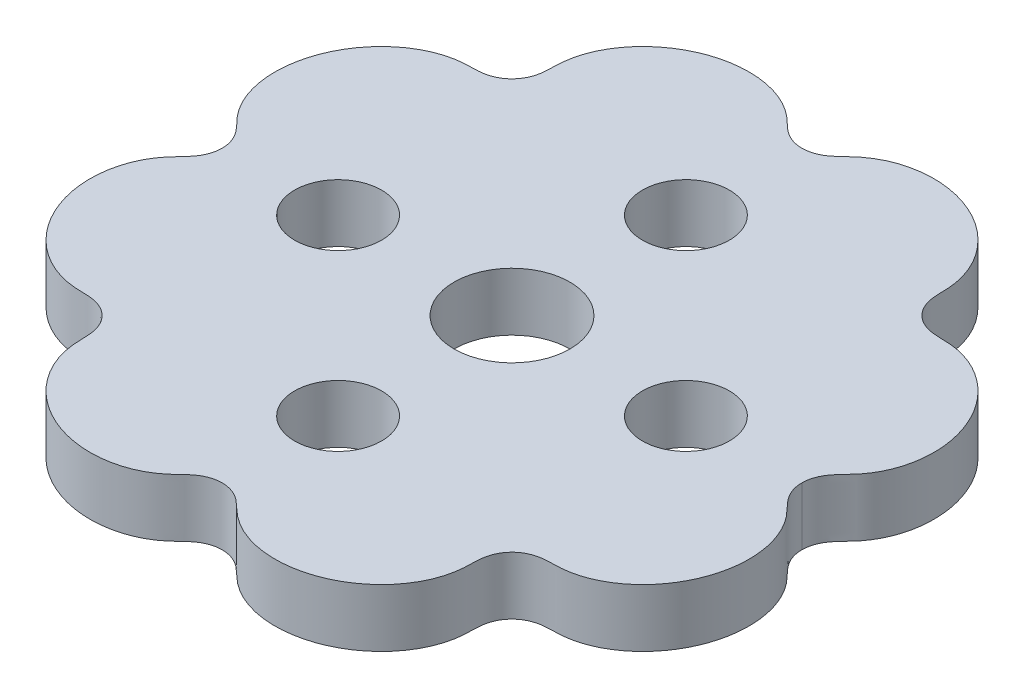
SolidWorks part; units mm, degrees
ref_plane "Front Plane" through (0, 0, 0) normal (0, 0, 1) x (1, 0, 0)
ref_plane "Top Plane" through (0, 0, 0) normal (0, 1, 0) x (1, 0, 0)
ref_plane "Right Plane" through (0, 0, 0) normal (1, 0, 0) x (0, 0, -1)
sketch "Sketch5" plane through (0, 0, 0) normal (0, 1, 0) x (1, 0, 0)
  line L0 (-32.3493, 0) -> (56.6401, 0)
  spline S0 degree 4 poles (36.0653, 9.3047) (36.0368, 8.9191) (35.9433, 8.1505) (35.7337, 7.203) (35.3376, 6.1094) (34.9089, 5.2416) (34.5065, 4.58) (34.1196, 4.0577) (33.7784, 3.6589) (33.5066, 3.3652) (33.3161, 3.1657) (33.1249, 2.9669) (32.9362, 2.7657) (32.7536, 2.5589) (32.5801, 2.3444) (32.3793, 2.0665) (32.202, 1.7738) (32.0526, 1.467) (31.9459, 1.1822) (31.887, 0.9906) (31.8463, 0.8311) (31.8188, 0.7051) (31.7958, 0.5778) (31.7774, 0.4503) (31.7635, 0.3244) (31.7542, 0.1917) (31.7496, 0.0468) (31.7496, -0.0355) (31.7525, -0.1372) (31.7593, -0.2706) (31.77, -0.3933) (31.7872, -0.5249) (31.8178, -0.7023) (31.856, -0.877) (31.9138, -1.0863) (31.9982, -1.3269) (32.1289, -1.6309) (32.3249, -1.9904) (32.5992, -2.3842) (32.9599, -2.7986) (33.3443, -3.1932) (33.7512, -3.623) (34.1594, -4.1069) (34.5532, -4.6541) (34.9206, -5.2674) (35.3166, -6.0684) (35.6909, -7.0746) (35.9833, -8.2938) (36.1265, -9.719) (36.0857, -11.1505) (35.8679, -12.5657) (35.4759, -13.959) (34.9113, -15.3088) (34.1765, -16.5924) (33.2755, -17.7852) (32.2272, -18.8511) (31.0442, -19.7662) (29.9051, -20.4113) (28.867, -20.834) (27.9695, -21.0883) (27.3282, -21.2114) (26.7726, -21.2762) (26.2753, -21.3075) (25.8378, -21.3198) (25.368, -21.326) (24.8659, -21.3537) (24.2397, -21.4445) (23.5136, -21.6686) (22.6692, -22.1561) (22.012, -22.8809) (21.6299, -23.6276) (21.4391, -24.3075) (21.3607, -24.7977) (21.33, -25.2669) (21.3212, -25.7113) (21.3125, -26.1301) (21.2939, -26.5232) (21.2515, -27.0133) (21.1656, -27.5976) (21.0127, -28.2699) (20.7698, -29.0194) (20.3873, -29.9268) (19.812, -30.9608) (18.992, -32.0732) (17.8827, -33.1968) (16.6299, -34.1571) (15.2753, -34.9326) (13.8479, -35.5184) (12.3743, -35.9118) (10.8798, -36.1113) (9.3717, -36.1132) (7.8771, -35.9092) (6.6082, -35.5435) (5.5718, -35.0916) (4.7569, -34.6212) (4.2175, -34.2432) (3.7806, -33.8862) (3.4136, -33.5539) (3.106, -33.2588) (2.781, -32.9456) (2.4211, -32.6326) (1.9211, -32.2705) (1.2506, -31.9282) (0.3937, -31.7122) (-0.6315, -31.7465) (-1.483, -32.0216) (-2.1427, -32.412) (-2.6466, -32.8217) (-3.0234, -33.1774) (-3.4322, -33.5748) (-3.8964, -33.9902) (-4.4316, -34.4023) (-5.0441, -34.7953) (-5.8481, -35.2209) (-6.863, -35.6267) (-8.0979, -35.95) (-9.5462, -36.1205) (-11.0039, -36.0995) (-12.4471, -35.8944) (-13.859, -35.5111) (-15.2183, -34.9553) (-16.5036, -34.2336) (-17.6929, -33.3532) (-18.7597, -32.3275) (-19.6808, -31.1687) (-20.3368, -30.0513) (-20.7737, -29.0314) (-21.0435, -28.1484) (-21.1793, -27.5164) (-21.256, -26.968) (-21.2974, -26.4734) (-21.3163, -26.0345) (-21.3226, -25.5605) (-21.339, -25.0512) (-21.4089, -24.4033) (-21.6068, -23.6543) (-22.0279, -22.8547) (-22.7451, -22.1123) (-23.5137, -21.6685) (-24.2396, -21.4446) (-24.866, -21.3537) (-25.368, -21.326) (-25.8378, -21.3198) (-26.2752, -21.3075) (-26.7726, -21.2762) (-27.3282, -21.2114) (-27.9695, -21.0883) (-28.867, -20.834) (-29.9051, -20.4113) (-31.0442, -19.7662) (-32.2272, -18.8511) (-33.2755, -17.7852) (-34.1765, -16.5924) (-34.9113, -15.3088) (-35.4759, -13.959) (-35.8679, -12.5657) (-36.0857, -11.1505) (-36.1265, -9.719) (-35.9833, -8.2938) (-35.6909, -7.0746) (-35.3166, -6.0684) (-34.9206, -5.2674) (-34.5532, -4.6541) (-34.1594, -4.1069) (-33.7512, -3.623) (-33.3443, -3.1932) (-32.9599, -2.7986) (-32.5992, -2.3842) (-32.3249, -1.9904) (-32.1289, -1.6309) (-31.9982, -1.3269) (-31.9237, -1.1144) (-31.8719, -0.9346) (-31.8369, -0.7897) (-31.8127, -0.6727) (-31.7923, -0.5548) (-31.7758, -0.4373) (-31.7647, -0.3337) (-31.7576, -0.2385) (-31.7525, -0.1372) (-31.7496, -0.0356) (-31.7496, 0.0468) (-31.7542, 0.1917) (-31.7635, 0.3244) (-31.7774, 0.4503) (-31.7958, 0.5778) (-31.8188, 0.7051) (-31.8463, 0.8311) (-31.887, 0.9906) (-31.9459, 1.1822) (-32.0287, 1.4034) (-32.142, 1.6505) (-32.2725, 1.8901) (-32.4191, 2.1215) (-32.6205, 2.4003) (-32.8423, 2.6647) (-33.0771, 2.9172) (-33.3639, 3.2154) (-33.6876, 3.555) (-34.0785, 4.0022) (-34.5065, 4.58) (-34.909, 5.2416) (-35.3376, 6.1094) (-35.7337, 7.203) (-35.9433, 8.1505) (-36.0368, 8.9191) (-36.0653, 9.3047) knots 0 0 0 0 0 0.010432 0.020864 0.026079 0.031295 0.036511 0.041727 0.043587 0.045447 0.047307 0.049167 0.051027 0.052888 0.054748 0.056608 0.060272 0.062104 0.063936 0.064805 0.065675 0.066545 0.067415 0.068285 0.069155 0.070025 0.070895 0.071768 0.072204 0.072641 0.07425 0.075055 0.07586 0.077469 0.079079 0.080906 0.082734 0.086389 0.090104 0.09382 0.097536 0.101251 0.106068 0.110884 0.1157 0.120516 0.130148 0.13978 0.149413 0.159045 0.168678 0.17831 0.188364 0.198418 0.208471 0.218525 0.228579 0.238633 0.243659 0.248685 0.253712 0.256225 0.258738 0.262126 0.265515 0.268903 0.272291 0.279171 0.285885 0.294871 0.298212 0.301553 0.304894 0.308235 0.310888 0.313542 0.316195 0.318848 0.324155 0.329461 0.334768 0.340075 0.350688 0.361302 0.371915 0.382528 0.393142 0.403282 0.413423 0.423563 0.433704 0.443844 0.453984 0.459054 0.464124 0.469194 0.471729 0.474264 0.477478 0.480691 0.483905 0.487119 0.494104 0.500875 0.507427 0.514443 0.517937 0.52143 0.524924 0.528417 0.53332 0.538222 0.543124 0.548026 0.557832 0.567637 0.577442 0.587247 0.597053 0.606858 0.61681 0.626763 0.636715 0.646668 0.65662 0.666572 0.671548 0.676524 0.6815 0.683988 0.686476 0.689911 0.693345 0.69678 0.700214 0.707466 0.714115 0.720829 0.727709 0.731097 0.734485 0.737874 0.741262 0.743775 0.746288 0.751315 0.756341 0.761367 0.771421 0.781475 0.791529 0.801582 0.811636 0.82169 0.831322 0.840955 0.850587 0.86022 0.869852 0.879484 0.8843 0.889116 0.893932 0.898749 0.902464 0.90618 0.909896 0.913611 0.917266 0.919094 0.920921 0.922531 0.923336 0.92414 0.924945 0.92575 0.926554 0.927359 0.927796 0.928232 0.929105 0.929975 0.930845 0.931715 0.932585 0.933455 0.934325 0.935195 0.936064 0.937896 0.939728 0.94156 0.943392 0.945252 0.947112 0.950833 0.952693 0.954553 0.958273 0.963489 0.968705 0.973921 0.979136 0.989568 1 1 1 1 1 construction
  spline S1 degree 4 poles (31.75, 0) (31.75, -0.0278) (31.7506, -0.0693) (31.7525, -0.1372) (31.7593, -0.2706) (31.77, -0.3933) (31.7872, -0.5249) (31.8178, -0.7023) (31.856, -0.877) (31.9138, -1.0863) (31.9982, -1.3269) (32.1289, -1.6309) (32.3249, -1.9904) (32.5992, -2.3842) (32.9599, -2.7986) (33.3443, -3.1932) (33.7512, -3.623) (34.1594, -4.1069) (34.5532, -4.6541) (34.9206, -5.2674) (35.3166, -6.0684) (35.6909, -7.0746) (35.9833, -8.2938) (36.1265, -9.719) (36.0857, -11.1505) (35.8679, -12.5657) (35.4759, -13.959) (34.9113, -15.3088) (34.1765, -16.5924) (33.2755, -17.7852) (32.2272, -18.8511) (31.0442, -19.7662) (29.9051, -20.4113) (28.867, -20.834) (27.9695, -21.0883) (27.3282, -21.2114) (26.7726, -21.2762) (26.2753, -21.3075) (25.8378, -21.3198) (25.368, -21.326) (24.8659, -21.3537) (24.2397, -21.4445) (23.5136, -21.6686) (22.6692, -22.1561) (22.012, -22.8809) (21.6299, -23.6276) (21.4391, -24.3075) (21.3607, -24.7977) (21.33, -25.2669) (21.3212, -25.7113) (21.3125, -26.1301) (21.2939, -26.5232) (21.2515, -27.0133) (21.1656, -27.5976) (21.0127, -28.2699) (20.7698, -29.0194) (20.3873, -29.9268) (19.812, -30.9608) (18.992, -32.0732) (17.8827, -33.1968) (16.6299, -34.1571) (15.2753, -34.9326) (13.8479, -35.5184) (12.3743, -35.9118) (10.8798, -36.1113) (9.3717, -36.1132) (7.8771, -35.9092) (6.6082, -35.5435) (5.5718, -35.0916) (4.7569, -34.6212) (4.2175, -34.2432) (3.7806, -33.8862) (3.4136, -33.5539) (3.106, -33.2588) (2.781, -32.9456) (2.4211, -32.6326) (1.9211, -32.2705) (1.2506, -31.9282) (0.3937, -31.7122) (-0.6315, -31.7465) (-1.483, -32.0216) (-2.1427, -32.412) (-2.6466, -32.8217) (-3.0234, -33.1774) (-3.4322, -33.5748) (-3.8964, -33.9902) (-4.4316, -34.4023) (-5.0441, -34.7953) (-5.8481, -35.2209) (-6.863, -35.6267) (-8.0979, -35.95) (-9.5462, -36.1205) (-11.0039, -36.0995) (-12.4471, -35.8944) (-13.859, -35.5111) (-15.2183, -34.9553) (-16.5036, -34.2336) (-17.6929, -33.3532) (-18.7597, -32.3275) (-19.6808, -31.1687) (-20.3368, -30.0513) (-20.7737, -29.0314) (-21.0435, -28.1484) (-21.1793, -27.5164) (-21.256, -26.968) (-21.2974, -26.4734) (-21.3163, -26.0345) (-21.3226, -25.5605) (-21.339, -25.0512) (-21.4089, -24.4033) (-21.6068, -23.6543) (-22.0279, -22.8547) (-22.7451, -22.1123) (-23.5137, -21.6685) (-24.2396, -21.4446) (-24.866, -21.3537) (-25.368, -21.326) (-25.8378, -21.3198) (-26.2752, -21.3075) (-26.7726, -21.2762) (-27.3282, -21.2114) (-27.9695, -21.0883) (-28.867, -20.834) (-29.9051, -20.4113) (-31.0442, -19.7662) (-32.2272, -18.8511) (-33.2755, -17.7852) (-34.1765, -16.5924) (-34.9113, -15.3088) (-35.4759, -13.959) (-35.8679, -12.5657) (-36.0857, -11.1505) (-36.1265, -9.719) (-35.9833, -8.2938) (-35.6909, -7.0746) (-35.3166, -6.0684) (-34.9206, -5.2674) (-34.5532, -4.6541) (-34.1594, -4.1069) (-33.7512, -3.623) (-33.3443, -3.1932) (-32.9599, -2.7986) (-32.5992, -2.3842) (-32.3249, -1.9904) (-32.1289, -1.6309) (-31.9982, -1.3269) (-31.9237, -1.1144) (-31.8719, -0.9346) (-31.8369, -0.7897) (-31.8127, -0.6727) (-31.7923, -0.5548) (-31.7758, -0.4373) (-31.7647, -0.3337) (-31.7576, -0.2385) (-31.7525, -0.1372) (-31.7506, -0.0693) (-31.75, -0.0278) (-31.75, 0) knots 0.070895 0.070895 0.070895 0.070895 0.070895 0.071768 0.072204 0.072641 0.07425 0.075055 0.07586 0.077469 0.079079 0.080906 0.082734 0.086389 0.090104 0.09382 0.097536 0.101251 0.106068 0.110884 0.1157 0.120516 0.130148 0.13978 0.149413 0.159045 0.168678 0.17831 0.188364 0.198418 0.208471 0.218525 0.228579 0.238633 0.243659 0.248685 0.253712 0.256225 0.258738 0.262126 0.265515 0.268903 0.272291 0.279171 0.285885 0.294871 0.298212 0.301553 0.304894 0.308235 0.310888 0.313542 0.316195 0.318848 0.324155 0.329461 0.334768 0.340075 0.350688 0.361302 0.371915 0.382528 0.393142 0.403282 0.413423 0.423563 0.433704 0.443844 0.453984 0.459054 0.464124 0.469194 0.471729 0.474264 0.477478 0.480691 0.483905 0.487119 0.494104 0.500875 0.507427 0.514443 0.517937 0.52143 0.524924 0.528417 0.53332 0.538222 0.543124 0.548026 0.557832 0.567637 0.577442 0.587247 0.597053 0.606858 0.61681 0.626763 0.636715 0.646668 0.65662 0.666572 0.671548 0.676524 0.6815 0.683988 0.686476 0.689911 0.693345 0.69678 0.700214 0.707466 0.714115 0.720829 0.727709 0.731097 0.734485 0.737874 0.741262 0.743775 0.746288 0.751315 0.756341 0.761367 0.771421 0.781475 0.791529 0.801582 0.811636 0.82169 0.831322 0.840955 0.850587 0.86022 0.869852 0.879484 0.8843 0.889116 0.893932 0.898749 0.902464 0.90618 0.909896 0.913611 0.917266 0.919094 0.920921 0.922531 0.923336 0.92414 0.924945 0.92575 0.926554 0.927359 0.927796 0.928232 0.929105 0.929105 0.929105 0.929105 0.929105
extrude "Boss-Extrude4" add sketch "Sketch5" along normal blind 6.35
mirror "Mirror1" about plane through (0, 6.35, 0) normal (0, 0, -1) of "Boss-Extrude4"
sketch "Sketch8" plane through (0, 0, 0) normal (0, 1, 0) x (1, 0, 0)
  circle A0 centre (0, 0) radius 6.35
  dimension "D1" = 12.7
extrude "Cut-Extrude3" cut sketch "Sketch8" along normal through all
sketch "Sketch9" plane through (0, 6.35, 0) normal (0, 1, 0) x (1, 0, 0)
  line L0 (0, 0) -> (-36.7822, 0) construction
  line L1 (0, 0) -> (-19.05, 0) construction
  circle A0 centre (-19.05, 0) radius 4.7625
  dimension "D2" = 9.525
  dimension "D1" = 19.05
  dimension "D3" = 0
extrude "Cut-Extrude4" cut sketch "Sketch9" against normal blind 6.35
pattern_circular "CirPattern1" count 4 over 360 about axis through (0, 0, 0) along (0, 1, 0) of "Cut-Extrude4"
sketch "Sketch10" plane through (0, 0, 0) normal (0, 1, 0) x (1, 0, 0)
  circle A0 centre (0, 0) radius 38.1 construction
  dimension "D1" = 76.2
equation "\"R\"= 1.5in'radius of rotor"
equation "\"E\"= .125in'eccentricity"
equation "\"R_r\"= .125in'radius of roller"
equation "\"N\"= 9'number of rollers"
equation "\"R_o\"= .125in'output disk pin diameter"
equation "\"D2@Sketch9\"=\"E\"+\"R_o\"*2"
equation "\"D1@CirPattern1\"=4"
equation "\"D1@Sketch10\"=\"R\"*2"
equation "\"D1@Sketch9\"=\"R_off\""
equation "\"R_off\"= .75"
